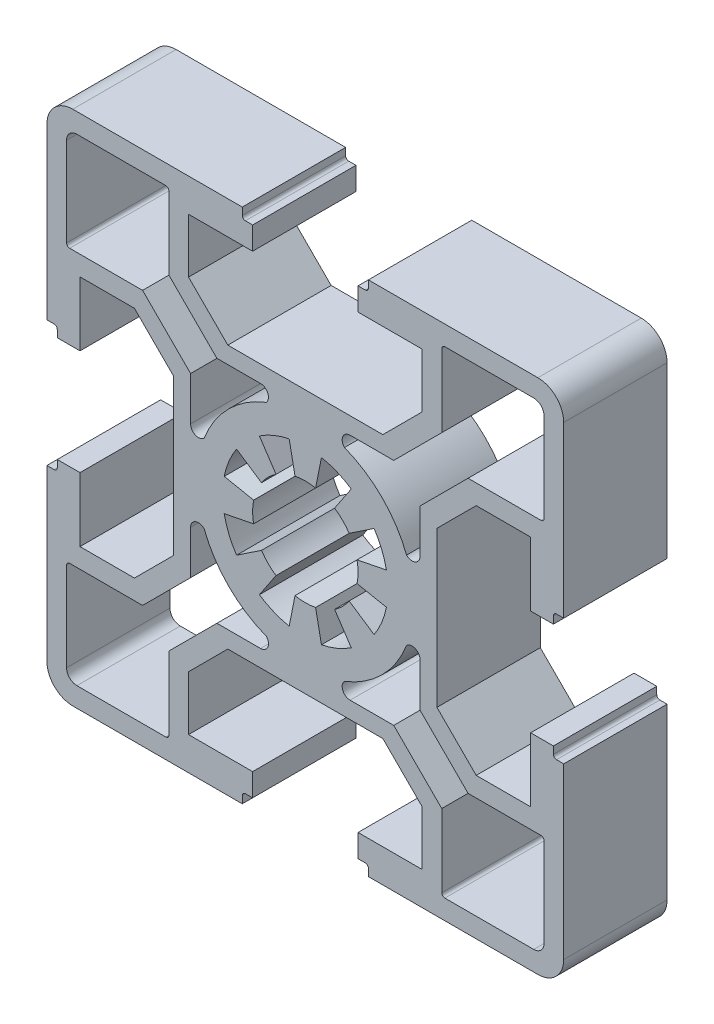
SolidWorks part; units mm, degrees
ref_plane "前视基准面" through (0, 0, 0) normal (0, 0, 1) x (1, 0, 0)
ref_plane "上视基准面" through (0, 0, 0) normal (0, 1, 0) x (1, 0, 0)
ref_plane "右视基准面" through (0, 0, 0) normal (1, 0, 0) x (0, 0, -1)
sketch "草图1" plane through (0, 0, 0) normal (0, 0, 1) x (1, 0, 0)
  line L0 (19.0095, -9.5291) -> (19.0095, -13.7515)
  line L1 (19.0095, -13.7515) -> (23.6551, -18.397)
  line L2 (23.6551, -18.397) -> (30.7095, -18.397)
  line L3 (31.0095, -18.697) -> (31.0095, -27.297)
  line L4 (30.0095, -28.297) -> (21.4095, -28.297)
  line L5 (21.1095, -27.997) -> (21.1095, -20.9426)
  line L6 (21.1095, -20.9426) -> (16.464, -16.297)
  line L7 (16.464, -16.297) -> (12.2416, -16.297)
  line L8 (12.2416, 5.903) -> (16.464, 5.903)
  line L9 (16.464, 5.903) -> (21.1095, 10.5485)
  line L10 (21.1095, 10.5485) -> (21.1095, 17.603)
  line L11 (21.4095, 17.903) -> (30.0095, 17.903)
  line L12 (31.0095, 16.903) -> (31.0095, 8.303)
  line L13 (30.7095, 8.003) -> (23.6551, 8.003)
  line L14 (23.6551, 8.003) -> (19.0095, 3.3574)
  line L15 (19.0095, 3.3574) -> (19.0095, -0.865)
  line L16 (3.5775, -16.297) -> (-0.6449, -16.297)
  line L17 (-0.6449, -16.297) -> (-5.2905, -20.9426)
  line L18 (-5.2905, -20.9426) -> (-5.2905, -27.997)
  line L19 (-5.5905, -28.297) -> (-14.1905, -28.297)
  line L20 (-15.1905, -27.297) -> (-15.1905, -18.697)
  line L21 (-14.8905, -18.397) -> (-7.836, -18.397)
  line L22 (-7.836, -18.397) -> (-3.1905, -13.7515)
  line L23 (-3.1905, -13.7515) -> (-3.1905, -9.5291)
  line L24 (1.2578, -0.7525) -> (3.669, -2.3636)
  line L25 (5.0761, -0.9565) -> (3.465, 1.4547)
  line L26 (6.3488, 2.6492) -> (6.9146, -0.195)
  line L27 (8.9045, -0.195) -> (9.4703, 2.6492)
  line L28 (12.3541, 1.4547) -> (10.7429, -0.9565)
  line L29 (12.15, -2.3636) -> (14.5613, -0.7525)
  line L30 (15.7558, -3.6363) -> (12.9115, -4.2021)
  line L31 (12.9115, -6.192) -> (15.7558, -6.7578)
  line L32 (14.5613, -9.6416) -> (12.15, -8.0305)
  line L33 (10.7429, -9.4375) -> (12.3541, -11.8488)
  line L34 (9.4703, -13.0433) -> (8.9045, -10.199)
  line L35 (6.9146, -10.199) -> (6.3488, -13.0433)
  line L36 (3.465, -11.8488) -> (5.0761, -9.4375)
  line L37 (3.669, -8.0305) -> (1.2578, -9.6416)
  line L38 (0.0633, -6.7578) -> (2.9075, -6.192)
  line L39 (2.9075, -4.2021) -> (0.0633, -3.6363)
  line L40 (-3.1905, -0.865) -> (-3.1905, 3.3574)
  line L41 (-3.1905, 3.3574) -> (-7.836, 8.003)
  line L42 (-7.836, 8.003) -> (-14.8905, 8.003)
  line L43 (-15.1905, 8.303) -> (-15.1905, 16.903)
  line L44 (-14.1905, 17.903) -> (-5.5905, 17.903)
  line L45 (-5.2905, 17.603) -> (-5.2905, 10.5485)
  line L46 (-5.2905, 10.5485) -> (-0.6449, 5.903)
  line L47 (-0.6449, 5.903) -> (3.5775, 5.903)
  line L48 (20.6421, 2.303) -> (24.4421, 6.103)
  line L49 (24.4421, 6.103) -> (29.7095, 6.103)
  line L50 (29.7095, 6.103) -> (29.7095, -0.097)
  line L51 (29.7095, -0.097) -> (31.9095, -0.097)
  line L52 (31.9095, -0.097) -> (31.9095, 0.603)
  line L53 (32.2095, 0.903) -> (32.9095, 0.903)
  line L54 (32.9095, 0.903) -> (32.9095, 17.303)
  line L55 (30.4095, 19.803) -> (14.0095, 19.803)
  line L56 (14.0095, 19.803) -> (14.0095, 19.103)
  line L57 (13.7095, 18.803) -> (13.0095, 18.803)
  line L58 (13.0095, 18.803) -> (13.0095, 16.603)
  line L59 (13.0095, 16.603) -> (19.2095, 16.603)
  line L60 (19.2095, 16.603) -> (19.2095, 11.3355)
  line L61 (19.2095, 11.3355) -> (15.4095, 7.5355)
  line L62 (15.4095, 7.5355) -> (7.9095, 7.5355)
  line L63 (7.9095, 7.5355) -> (0.4095, 7.5355)
  line L64 (0.4095, 7.5355) -> (-3.3905, 11.3355)
  line L65 (-3.3905, 11.3355) -> (-3.3905, 16.603)
  line L66 (-3.3905, 16.603) -> (2.8095, 16.603)
  line L67 (2.8095, 16.603) -> (2.8095, 18.803)
  line L68 (2.8095, 18.803) -> (2.1095, 18.803)
  line L69 (1.8095, 19.103) -> (1.8095, 19.803)
  line L70 (1.8095, 19.803) -> (-14.5905, 19.803)
  line L71 (-17.0905, 17.303) -> (-17.0905, 0.903)
  line L72 (-17.0905, 0.903) -> (-16.3905, 0.903)
  line L73 (-16.0905, 0.603) -> (-16.0905, -0.097)
  line L74 (-16.0905, -0.097) -> (-13.8905, -0.097)
  line L75 (-13.8905, -0.097) -> (-13.8905, 6.103)
  line L76 (-13.8905, 6.103) -> (-8.6231, 6.103)
  line L77 (-8.6231, 6.103) -> (-4.8231, 2.303)
  line L78 (-4.8231, 2.303) -> (-4.8231, -5.197)
  line L79 (-4.8231, -5.197) -> (-4.8231, -12.697)
  line L80 (-4.8231, -12.697) -> (-8.6231, -16.497)
  line L81 (-8.6231, -16.497) -> (-13.8905, -16.497)
  line L82 (-13.8905, -16.497) -> (-13.8905, -10.297)
  line L83 (-13.8905, -10.297) -> (-16.0905, -10.297)
  line L84 (-16.0905, -10.297) -> (-16.0905, -10.997)
  line L85 (-16.3905, -11.297) -> (-17.0905, -11.297)
  line L86 (-17.0905, -11.297) -> (-17.0905, -27.697)
  line L87 (-14.5905, -30.197) -> (1.8095, -30.197)
  line L88 (1.8095, -30.197) -> (1.8095, -29.497)
  line L89 (2.1095, -29.197) -> (2.8095, -29.197)
  line L90 (2.8095, -29.197) -> (2.8095, -26.997)
  line L91 (2.8095, -26.997) -> (-3.3905, -26.997)
  line L92 (-3.3905, -26.997) -> (-3.3905, -21.7296)
  line L93 (-3.3905, -21.7296) -> (0.4095, -17.9296)
  line L94 (0.4095, -17.9296) -> (7.9095, -17.9296)
  line L95 (7.9095, -17.9296) -> (15.4095, -17.9296)
  line L96 (15.4095, -17.9296) -> (19.2095, -21.7296)
  line L97 (19.2095, -21.7296) -> (19.2095, -26.997)
  line L98 (19.2095, -26.997) -> (13.0095, -26.997)
  line L99 (13.0095, -26.997) -> (13.0095, -29.197)
  line L100 (13.0095, -29.197) -> (13.7095, -29.197)
  line L101 (14.0095, -29.497) -> (14.0095, -30.197)
  line L102 (14.0095, -30.197) -> (30.4095, -30.197)
  line L103 (32.9095, -27.697) -> (32.9095, -11.297)
  line L104 (32.9095, -11.297) -> (32.2095, -11.297)
  line L105 (31.9095, -10.997) -> (31.9095, -10.297)
  line L106 (31.9095, -10.297) -> (29.7095, -10.297)
  line L107 (29.7095, -10.297) -> (29.7095, -16.497)
  line L108 (29.7095, -16.497) -> (24.4421, -16.497)
  line L109 (24.4421, -16.497) -> (20.6421, -12.697)
  line L110 (20.6421, -12.697) -> (20.6421, -5.197)
  line L111 (20.6421, -5.197) -> (20.6421, 2.303)
  arc A0 (11.6941, -14.9913) -> (17.7038, -8.9816) centre (7.9095, -5.197) ccw
  arc A1 (19.0095, -9.5291) -> (17.7038, -8.9816) centre (18.2419, -9.5291) ccw
  arc A2 (31.0095, -18.697) -> (30.7095, -18.397) centre (30.7095, -18.697) ccw
  arc A3 (30.0095, -28.297) -> (31.0095, -27.297) centre (30.0095, -27.297) ccw
  arc A4 (21.1095, -27.997) -> (21.4095, -28.297) centre (21.4095, -27.997) ccw
  arc A5 (11.6941, -14.9913) -> (12.2416, -16.297) centre (12.2416, -15.5294) ccw
  arc A6 (21.4095, 17.903) -> (21.1095, 17.603) centre (21.4095, 17.603) ccw
  arc A7 (31.0095, 16.903) -> (30.0095, 17.903) centre (30.0095, 16.903) ccw
  arc A8 (30.7095, 8.003) -> (31.0095, 8.303) centre (30.7095, 8.303) ccw
  arc A9 (17.7038, -1.4124) -> (19.0095, -0.865) centre (18.2419, -0.865) ccw
  arc A10 (17.7038, -1.4124) -> (11.6941, 4.5972) centre (7.9095, -5.197) ccw
  arc A11 (12.2416, 5.903) -> (11.6941, 4.5972) centre (12.2416, 5.1353) ccw
  arc A12 (-1.8847, -8.9816) -> (4.1249, -14.9913) centre (7.9095, -5.197) ccw
  arc A13 (3.5775, -16.297) -> (4.1249, -14.9913) centre (3.5775, -15.5294) ccw
  arc A14 (-5.5905, -28.297) -> (-5.2905, -27.997) centre (-5.5905, -27.997) ccw
  arc A15 (-15.1905, -27.297) -> (-14.1905, -28.297) centre (-14.1905, -27.297) ccw
  arc A16 (-14.8905, -18.397) -> (-15.1905, -18.697) centre (-14.8905, -18.697) ccw
  arc A17 (-1.8847, -8.9816) -> (-3.1905, -9.5291) centre (-2.4228, -9.5291) ccw
  arc A18 (1.2578, -0.7525) -> (0.0633, -3.6363) centre (7.9095, -5.197) ccw
  arc A19 (5.0761, -0.9565) -> (3.669, -2.3636) centre (7.9095, -5.197) ccw
  arc A20 (6.3488, 2.6492) -> (3.465, 1.4547) centre (7.9095, -5.197) ccw
  arc A21 (8.9045, -0.195) -> (6.9146, -0.195) centre (7.9095, -5.197) ccw
  arc A22 (12.3541, 1.4547) -> (9.4703, 2.6492) centre (7.9095, -5.197) ccw
  arc A23 (12.15, -2.3636) -> (10.7429, -0.9565) centre (7.9095, -5.197) ccw
  arc A24 (15.7558, -3.6363) -> (14.5613, -0.7525) centre (7.9095, -5.197) ccw
  arc A25 (12.9115, -6.192) -> (12.9115, -4.2021) centre (7.9095, -5.197) ccw
  arc A26 (14.5613, -9.6416) -> (15.7558, -6.7578) centre (7.9095, -5.197) ccw
  arc A27 (10.7429, -9.4375) -> (12.15, -8.0305) centre (7.9095, -5.197) ccw
  arc A28 (9.4703, -13.0433) -> (12.3541, -11.8488) centre (7.9095, -5.197) ccw
  arc A29 (6.9146, -10.199) -> (8.9045, -10.199) centre (7.9095, -5.197) ccw
  arc A30 (3.465, -11.8488) -> (6.3488, -13.0433) centre (7.9095, -5.197) ccw
  arc A31 (3.669, -8.0305) -> (5.0761, -9.4375) centre (7.9095, -5.197) ccw
  arc A32 (0.0633, -6.7578) -> (1.2578, -9.6416) centre (7.9095, -5.197) ccw
  arc A33 (2.9075, -4.2021) -> (2.9075, -6.192) centre (7.9095, -5.197) ccw
  arc A34 (-15.1905, 8.303) -> (-14.8905, 8.003) centre (-14.8905, 8.303) ccw
  arc A35 (-14.1905, 17.903) -> (-15.1905, 16.903) centre (-14.1905, 16.903) ccw
  arc A36 (-5.2905, 17.603) -> (-5.5905, 17.903) centre (-5.5905, 17.603) ccw
  arc A37 (4.1249, 4.5972) -> (3.5775, 5.903) centre (3.5775, 5.1353) ccw
  arc A38 (4.1249, 4.5972) -> (-1.8847, -1.4124) centre (7.9095, -5.197) ccw
  arc A39 (-3.1905, -0.865) -> (-1.8847, -1.4124) centre (-2.4228, -0.865) ccw
  arc A40 (32.2095, 0.903) -> (31.9095, 0.603) centre (32.2095, 0.603) ccw
  arc A41 (32.9095, 17.303) -> (30.4095, 19.803) centre (30.4095, 17.303) ccw
  arc A42 (13.7095, 18.803) -> (14.0095, 19.103) centre (13.7095, 19.103) ccw
  arc A43 (1.8095, 19.103) -> (2.1095, 18.803) centre (2.1095, 19.103) ccw
  arc A44 (-14.5905, 19.803) -> (-17.0905, 17.303) centre (-14.5905, 17.303) ccw
  arc A45 (-16.0905, 0.603) -> (-16.3905, 0.903) centre (-16.3905, 0.603) ccw
  arc A46 (-16.3905, -11.297) -> (-16.0905, -10.997) centre (-16.3905, -10.997) ccw
  arc A47 (-17.0905, -27.697) -> (-14.5905, -30.197) centre (-14.5905, -27.697) ccw
  arc A48 (2.1095, -29.197) -> (1.8095, -29.497) centre (2.1095, -29.497) ccw
  arc A49 (14.0095, -29.497) -> (13.7095, -29.197) centre (13.7095, -29.497) ccw
  arc A50 (30.4095, -30.197) -> (32.9095, -27.697) centre (30.4095, -27.697) ccw
  arc A51 (31.9095, -10.997) -> (32.2095, -11.297) centre (32.2095, -10.997) ccw
extrude "凸台-拉伸1" add sketch "草图1" along normal blind 10
